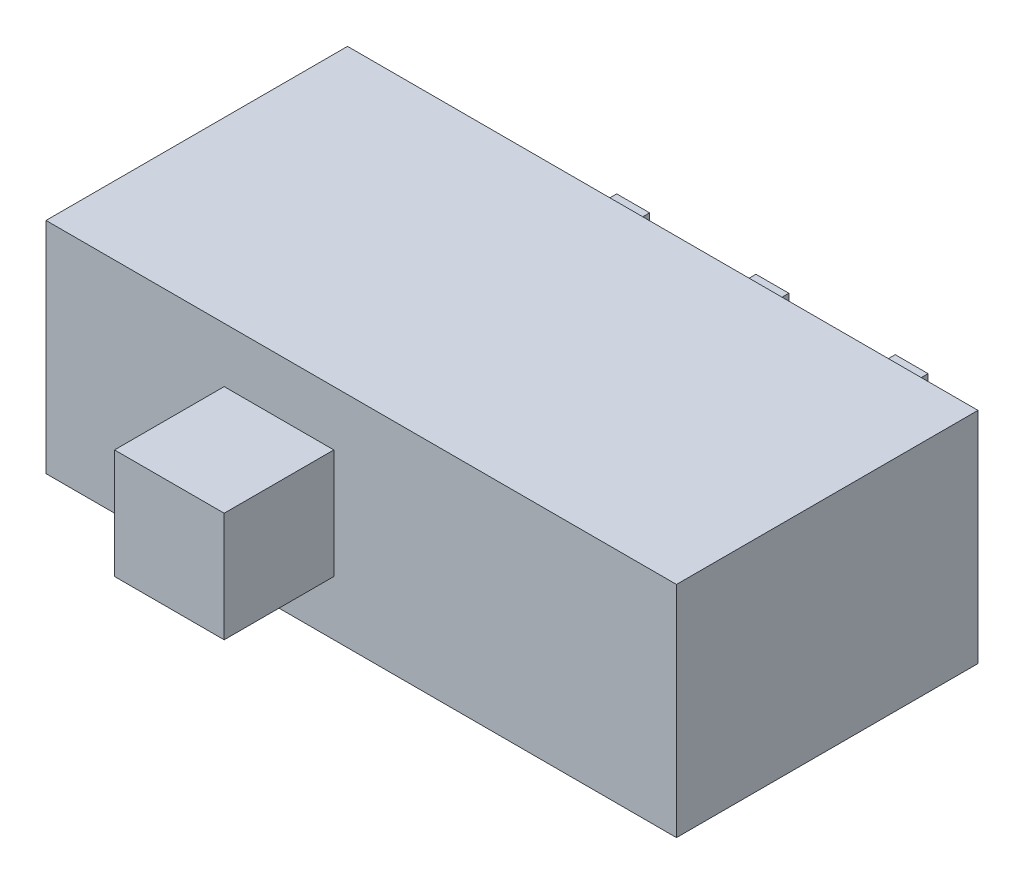
SolidWorks part; units mm, degrees
ref_plane "Front Plane" through (0, 0, 0) normal (0, 0, 1) x (1, 0, 0)
ref_plane "Top Plane" through (0, 0, 0) normal (0, 1, 0) x (1, 0, 0)
ref_plane "Right Plane" through (0, 0, 0) normal (1, 0, 0) x (0, 0, -1)
sketch "Sketch1" plane through (0, 0, 0) normal (0, 1, 0) x (1, 0, 0)
  line L1 (-5.75, -2.75) -> (5.75, -2.75)
  line L2 (-5.75, -2.75) -> (-5.75, 2.75)
  line L3 (-5.75, 2.75) -> (5.75, 2.75)
  line L4 (5.75, -2.75) -> (5.75, 2.75)
  line L5 (-5.75, -2.75) -> (5.75, 2.75) construction
  line L6 (-5.75, 2.75) -> (5.75, -2.75) construction
  point P0 (0, 0)
  dimension "D1" = 5.5
  dimension "D2" = 11.5
extrude "Boss-Extrude1" add sketch "Sketch1" along normal mid plane 4
sketch "Sketch4" plane through (0, 0, 2.75) normal (0, 0, 1) x (1, 0, 0)
  line L1 (-2.5, -1.1) -> (2.5, -1.1)
  line L2 (-2.5, -1.1) -> (-2.5, 1.1)
  line L3 (-2.5, 1.1) -> (2.5, 1.1)
  line L4 (2.5, -1.1) -> (2.5, 1.1)
  line L5 (-2.5, -1.1) -> (2.5, 1.1) construction
  line L6 (-2.5, 1.1) -> (2.5, -1.1) construction
  point P0 (0, 0)
  dimension "D1" = 2.2
  dimension "D2" = 5
sketch "Sketch3" plane through (0, 0, 2.75) normal (0, 0, 1) x (1, 0, 0)
  line L0 (-2.5, -1.1) -> (-2.5, 1.1) construction
  line L1 (-2.5, -1) -> (-0.5, -1)
  line L2 (-2.5, -1) -> (-2.5, 1)
  line L3 (-2.5, 1) -> (-0.5, 1)
  line L4 (-0.5, -1) -> (-0.5, 1)
  line L5 (-2.5, -1) -> (-0.5, 1) construction
  line L6 (-2.5, 1) -> (-0.5, -1) construction
  point P0 (-1.5, 0)
  dimension "D1" = 2
extrude "Boss-Extrude2" add sketch "Sketch3" along normal blind 2
sketch "Sketch5" plane through (0, 0, -2.75) normal (0, 0, -1) x (-1, 0, 0)
  line L0 (-2.84, -0.125) -> (-2.24, -0.125)
  line L1 (-0.3, -0.125) -> (0.3, -0.125)
  line L2 (-0.3, -0.125) -> (-0.3, 0.125)
  line L3 (-0.3, 0.125) -> (0.3, 0.125)
  line L4 (0.3, -0.125) -> (0.3, 0.125)
  line L5 (-0.3, -0.125) -> (0.3, 0.125) construction
  line L6 (-0.3, 0.125) -> (0.3, -0.125) construction
  line L7 (-2.84, -0.125) -> (-2.84, 0.125)
  line L8 (-2.84, 0.125) -> (-2.24, 0.125)
  line L9 (-2.24, -0.125) -> (-2.24, 0.125)
  line L10 (-2.84, -0.125) -> (-2.24, 0.125) construction
  line L11 (-2.84, 0.125) -> (-2.24, -0.125) construction
  line L12 (2.24, -0.125) -> (2.84, -0.125)
  line L13 (2.24, -0.125) -> (2.24, 0.125)
  line L14 (2.24, 0.125) -> (2.84, 0.125)
  line L15 (2.84, -0.125) -> (2.84, 0.125)
  line L16 (2.24, -0.125) -> (2.84, 0.125) construction
  line L17 (2.24, 0.125) -> (2.84, -0.125) construction
  point P0 (0, 0)
  point P6 (-2.54, 0)
  point P11 (2.54, 0)
  dimension "D1" = 0.6
  dimension "D2" = 0.25
  dimension "D3" = 0.6
  dimension "D4" = 0.25
  dimension "D5" = 0.6
  dimension "D6" = 0.25
  dimension "D7" = 2.54
  dimension "D8" = 2.54
extrude "Boss-Extrude3" add sketch "Sketch5" along normal blind 2
